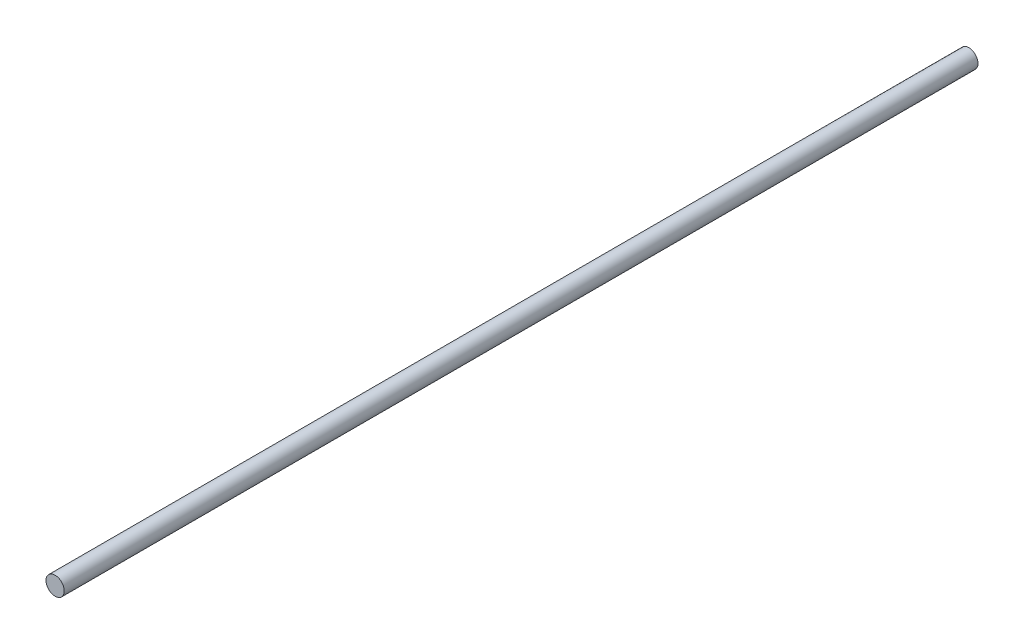
SolidWorks part; units mm, degrees
ref_plane "Front Plane" through (0, 0, 0) normal (0, 0, 1) x (1, 0, 0)
ref_plane "Top Plane" through (0, 0, 0) normal (0, 1, 0) x (1, 0, 0)
ref_plane "Right Plane" through (0, 0, 0) normal (1, 0, 0) x (0, 0, -1)
sketch "Sketch1" plane through (0, 0, 0) normal (0, 0, 1) x (1, 0, 0)
  circle A0 centre (0, 0) radius 4
  dimension "D1" = 8
extrude "Boss-Extrude1" add sketch "Sketch1" along normal blind 400
sketch "Sketch3" plane through (0, 0, 400) normal (0, 0, 1) x (1, 0, 0)
  circle A0 centre (0, 0) radius 4
curve "Helix/Spiral1" pitch 1.25 height 10 turns 8
sketch "Sketch4" plane through (0, 0, 0) normal (1, 0, 0) x (0, 0, -1)
  line L1 (-400, 3.2783) -> (-399.375, 4.3608) construction
  line L2 (-399.375, 4.3608) -> (-400.625, 4.3608) construction
  line L3 (-400.625, 4.3608) -> (-400, 3.2783) construction
  line L5 (-400.1563, 3.5489) -> (-399.8437, 3.5489) construction
  line L6 (-400.625, 4.3608) -> (-399.375, 4.3608)
  line L7 (-399.375, 4.3608) -> (-399.8437, 3.5489)
  line L8 (-399.8437, 3.5489) -> (-400.1563, 3.5489)
  line L9 (-400.1563, 3.5489) -> (-400.625, 4.3608)
  line L10 (-400, 4) -> (-400, -4) construction
  circle A0 centre (-400, 4) radius 0.3608 construction
  spline S0 degree 3 poles (-400, 4) (-399.9741, 4) (-399.9218, 3.7917) (-399.8438, 2.9021) (-399.7656, 1.5706) (-399.6875, 0) (-399.6094, -1.5706) (-399.5313, -2.9021) (-399.4531, -3.7917) (-399.375, -4.1041) (-399.2969, -3.7917) (-399.2188, -2.9021) (-399.1406, -1.5706) (-399.0625, 0) (-398.9844, 1.5706) (-398.9063, 2.9021) (-398.8281, 3.7917) (-398.75, 4.1041) (-398.6719, 3.7917) (-398.5937, 2.9021) (-398.5156, 1.5706) (-398.4375, 0) (-398.3594, -1.5706) (-398.2812, -2.9021) (-398.2031, -3.7917) (-398.125, -4.1041) (-398.0469, -3.7917) (-397.9688, -2.9021) (-397.8906, -1.5706) (-397.8125, 0) (-397.7344, 1.5706) (-397.6563, 2.9021) (-397.5781, 3.7917) (-397.5, 4.1041) (-397.4219, 3.7917) (-397.3438, 2.9021) (-397.2656, 1.5706) (-397.1875, 0) (-397.1094, -1.5706) (-397.0312, -2.9021) (-396.9531, -3.7917) (-396.875, -4.1041) (-396.7969, -3.7917) (-396.7188, -2.9021) (-396.6406, -1.5706) (-396.5625, 0) (-396.4844, 1.5706) (-396.4063, 2.9021) (-396.3281, 3.7917) (-396.25, 4.1041) (-396.1719, 3.7917) (-396.0937, 2.9021) (-396.0156, 1.5706) (-395.9375, 0) (-395.8594, -1.5706) (-395.7812, -2.9021) (-395.7031, -3.7917) (-395.625, -4.1041) (-395.5469, -3.7917) (-395.4688, -2.9021) (-395.3906, -1.5706) (-395.3125, 0) (-395.2344, 1.5706) (-395.1563, 2.9021) (-395.0781, 3.7917) (-395, 4.1041) (-394.9219, 3.7917) (-394.8438, 2.9021) (-394.7656, 1.5706) (-394.6875, 0) (-394.6094, -1.5706) (-394.5313, -2.9021) (-394.4531, -3.7917) (-394.375, -4.1041) (-394.2969, -3.7917) (-394.2187, -2.9021) (-394.1406, -1.5706) (-394.0625, 0) (-393.9844, 1.5706) (-393.9063, 2.9021) (-393.8281, 3.7917) (-393.75, 4.1041) (-393.6719, 3.7917) (-393.5937, 2.9021) (-393.5156, 1.5706) (-393.4375, 0) (-393.3594, -1.5706) (-393.2812, -2.9021) (-393.2031, -3.7917) (-393.125, -4.1041) (-393.0469, -3.7917) (-392.9688, -2.9021) (-392.8906, -1.5706) (-392.8125, 0) (-392.7344, 1.5706) (-392.6563, 2.9021) (-392.5781, 3.7917) (-392.5, 4.1041) (-392.4219, 3.7917) (-392.3438, 2.9021) (-392.2656, 1.5706) (-392.1875, 0) (-392.1094, -1.5706) (-392.0312, -2.9021) (-391.9531, -3.7917) (-391.875, -4.1041) (-391.7969, -3.7917) (-391.7188, -2.9021) (-391.6406, -1.5706) (-391.5625, 0) (-391.4844, 1.5706) (-391.4062, 2.9021) (-391.3281, 3.7917) (-391.25, 4.1041) (-391.1719, 3.7917) (-391.0937, 2.9021) (-391.0156, 1.5706) (-390.9375, 0) (-390.8594, -1.5706) (-390.7812, -2.9021) (-390.7031, -3.7917) (-390.625, -4.1041) (-390.5469, -3.7917) (-390.4687, -2.9021) (-390.3906, -1.5706) (-390.3125, 0) (-390.2344, 1.5706) (-390.1562, 2.9021) (-390.0782, 3.7917) (-390.0259, 4) (-390, 4) knots 0 0 0 0 0.007812 0.015625 0.023437 0.03125 0.039062 0.046875 0.054687 0.0625 0.070312 0.078125 0.085938 0.09375 0.101562 0.109375 0.117187 0.125 0.132812 0.140625 0.148437 0.15625 0.164062 0.171875 0.179687 0.1875 0.195312 0.203125 0.210937 0.21875 0.226562 0.234375 0.242187 0.25 0.257812 0.265625 0.273437 0.28125 0.289062 0.296875 0.304687 0.3125 0.320312 0.328125 0.335937 0.34375 0.351562 0.359375 0.367187 0.375 0.382812 0.390625 0.398437 0.40625 0.414062 0.421875 0.429687 0.4375 0.445312 0.453125 0.460937 0.46875 0.476562 0.484375 0.492187 0.5 0.507812 0.515625 0.523437 0.53125 0.539062 0.546875 0.554687 0.5625 0.570312 0.578125 0.585937 0.59375 0.601562 0.609375 0.617187 0.625 0.632812 0.640625 0.648437 0.65625 0.664062 0.671875 0.679687 0.6875 0.695312 0.703125 0.710937 0.71875 0.726562 0.734375 0.742187 0.75 0.757812 0.765625 0.773437 0.78125 0.789062 0.796875 0.804687 0.8125 0.820312 0.828125 0.835937 0.84375 0.851562 0.859375 0.867187 0.875 0.882812 0.890625 0.898437 0.90625 0.914062 0.921875 0.929687 0.9375 0.945312 0.953125 0.960937 0.96875 0.976562 0.984375 0.992187 1 1 1 1 construction
  dimension "D2" = 1.0825
  dimension "D3" = 0.2706
